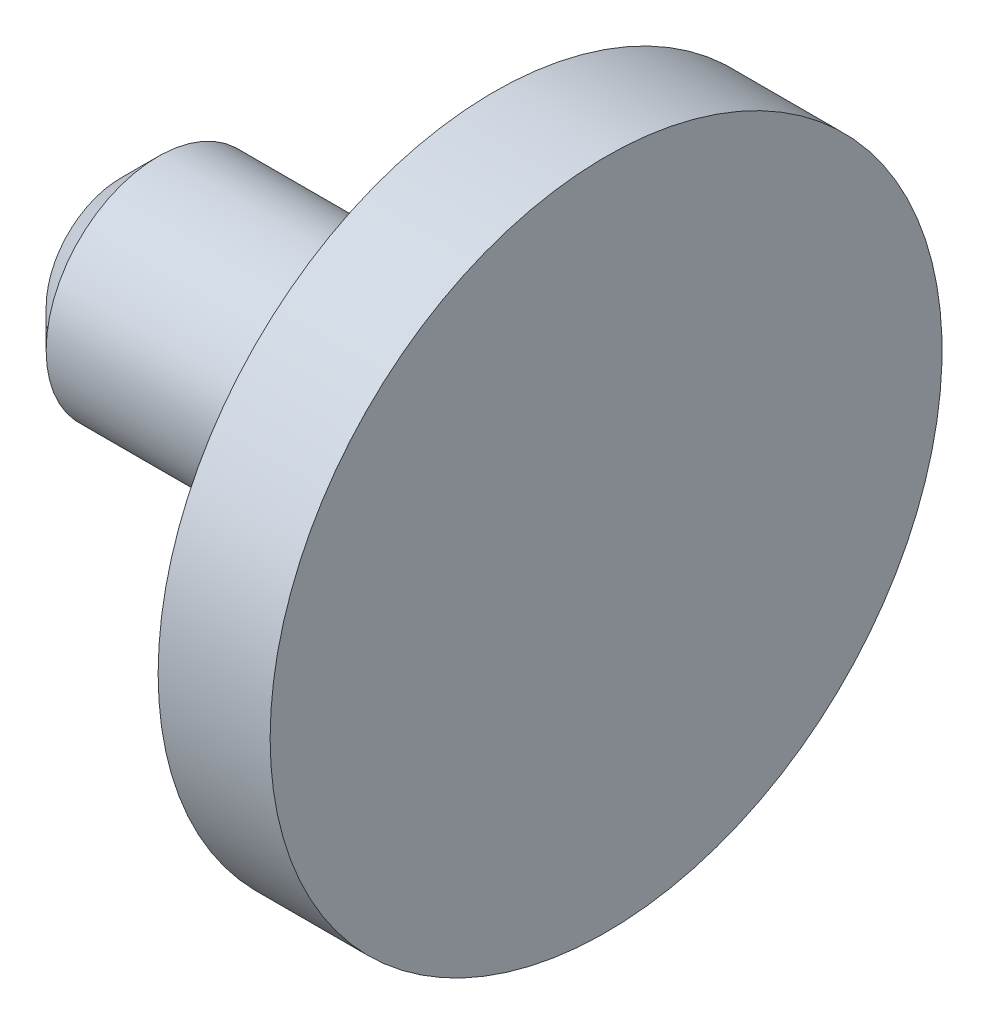
SolidWorks part; units mm, degrees
ref_plane "Plan1" through (0, 0, 0) normal (0, 0, 1) x (1, 0, 0)
ref_plane "Plan2" through (0, 0, 0) normal (0, 1, 0) x (1, 0, 0)
ref_plane "Plan3" through (0, 0, 0) normal (1, 0, 0) x (0, 0, -1)
sketch "Esquisse1" plane through (0, 0, 0) normal (0, 0, 1) x (1, 0, 0)
  line L0 (0, 0) -> (15.6166, 0) construction
  line L2 (0, 0) -> (0, 2)
  line L3 (1, 3) -> (10, 3)
  line L4 (0, 2) -> (1, 3)
  line L5 (0, 0) -> (13, 0)
  line L6 (10, 3) -> (10, 9)
  line L7 (10, 9) -> (13, 9)
  line L8 (13, 0) -> (13, 9)
  dimension "D1" = 9
  dimension "D2" = 3
  dimension "D3" = 3
  dimension "D4" = 45
  dimension "D5" = 1
  dimension "D6" = 10
revolve "Base-Révolution" add sketch "Esquisse1" angle 360 about L0
